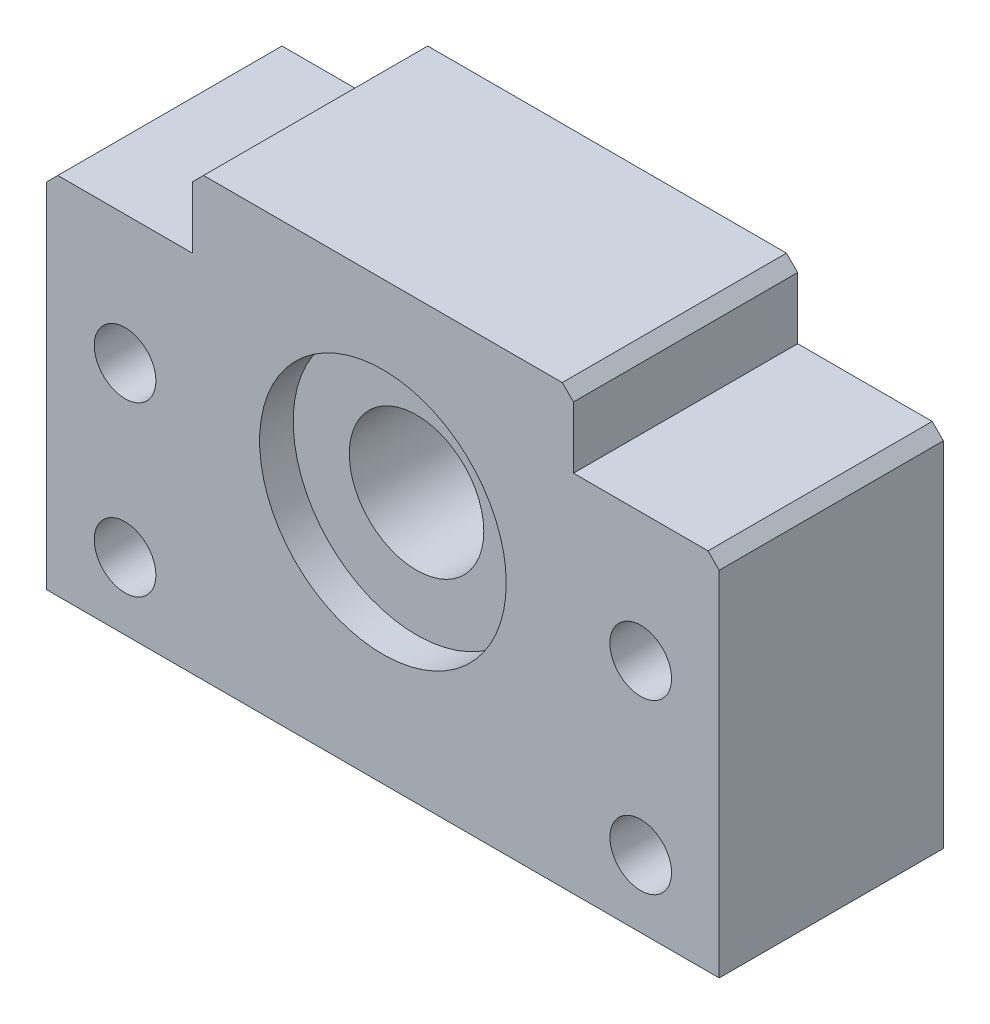
SolidWorks part; units mm, degrees
ref_plane "前视基准面" through (0, 0, 0) normal (0, 0, 1) x (1, 0, 0)
ref_plane "上视基准面" through (0, 0, 0) normal (0, 1, 0) x (1, 0, 0)
ref_plane "右视基准面" through (0, 0, 0) normal (1, 0, 0) x (0, 0, -1)
sketch "草图1" plane through (0, 0, 0) normal (0, 0, 1) x (1, 0, 0)
  line L0 (-30, 0) -> (30, 0)
  line L1 (30, 0) -> (30, 32.5)
  line L2 (30, 32.5) -> (17, 32.5)
  line L3 (17, 32.5) -> (17, 39)
  line L4 (17, 39) -> (-17, 39)
  line L5 (-17, 39) -> (-17, 32.5)
  line L6 (-17, 32.5) -> (-30, 32.5)
  line L7 (-30, 32.5) -> (-30, 0)
  dimension "D1" = 30
  dimension "D2" = 60
  dimension "D3" = 32.5
  dimension "D4" = 32.5
  dimension "D5" = 39
  dimension "D6" = 34
  dimension "D7" = 13
extrude "凸台-拉伸1" add sketch "草图1" along normal blind 20
chamfer "倒角1" distance 1 angle 45 1 edges at (17, 39, 10)
chamfer "倒角2" distance 1 angle 45 3 edges at (-30, 32.5, 10) (30, 32.5, 10) (-17, 39, 10)
sketch "草图2" plane through (0, 0, 20) normal (0, 0, 1) x (1, 0, 0)
  line L1 (-30, 31.5) -> (-30, 0) construction
  line L2 (16, 39) -> (-16, 39) construction
  circle A0 centre (-23, 21) radius 2.75
  circle A1 centre (-23, 6) radius 2.75
  dimension "D1" = 5.5
  dimension "D4" = 5.5
  dimension "D2" = 18
  dimension "D3" = 7
  dimension "D5" = 15
extrude "切除-拉伸1" cut sketch "草图2" against normal blind 20
mirror "镜向1" about plane through (0, 0, 0) normal (1, 0, 0) of "切除-拉伸1"
sketch "草图4" plane through (0, 0, 20) normal (0, 0, 1) x (1, 0, 0)
  line L0 (16, 39) -> (-16, 39) construction
  circle A0 centre (0, 21) radius 6
  dimension "D1" = 12
  dimension "D2" = 18
extrude "切除-拉伸2" cut sketch "草图4" against normal blind 20
sketch "草图5" plane through (0, 0, 20) normal (0, 0, 1) x (1, 0, 0)
  circle A0 centre (0, 21) radius 11
extrude "切除-拉伸3" cut sketch "草图5" against normal blind 3
sketch "草图6" plane through (-30, 0, 0) normal (-1, 0, 0) x (0, 0, 1)
  line L0 (10, -3.6962) -> (10, 44.9218) construction
sketch "草图7" plane through (30, 0, 0) normal (1, 0, 0) x (0, 0, -1)
  line L0 (-10, -3.6962) -> (-10, 44.9218) construction
ref_plane "基准面1" through (0, 0, 10) normal (0, 0, -1) x (-1, 0, 0)
mirror "镜向2" about plane through (0, 0, 10) normal (0, 0, -1) of "切除-拉伸3"
